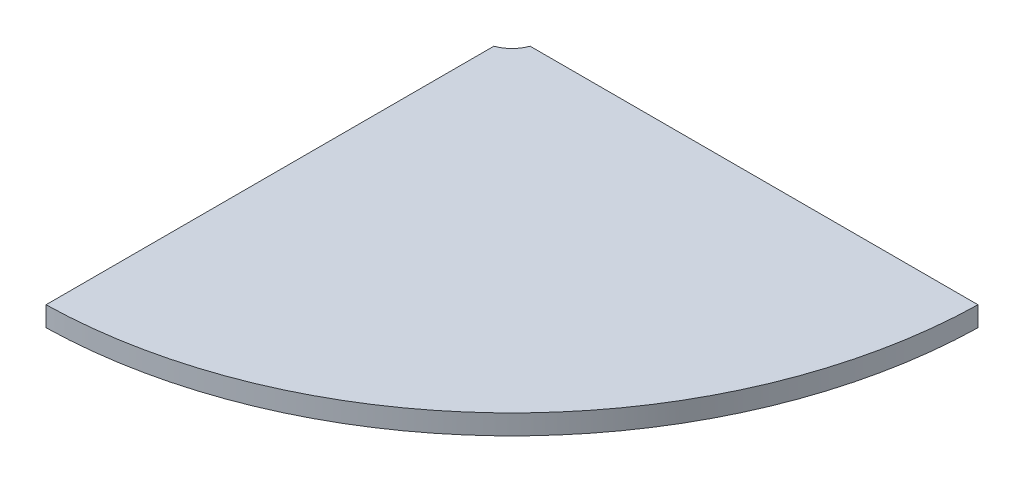
SolidWorks part; units mm, degrees
ref_plane "Alzado" through (0, 0, 0) normal (0, 0, 1) x (1, 0, 0)
ref_plane "Planta" through (0, 0, 0) normal (0, 1, 0) x (1, 0, 0)
ref_plane "Vista lateral" through (0, 0, 0) normal (1, 0, 0) x (0, 0, -1)
sketch "Croquis1" plane through (0, 0, 0) normal (0, 1, 0) x (1, 0, 0)
  line L0 (238.9081, -4.8752) -> (14.0133, -4.8752)
  line L1 (4.9081, -13.9804) -> (4.9081, -238.8752)
  line L2 (238.9081, -4.8752) -> (4.9081, -4.8752) construction
  line L3 (4.9081, -4.8752) -> (4.9081, -238.8752) construction
  arc A0 (4.9081, -238.8752) -> (238.9081, -4.8752) centre (-0.0718, 0.1047) ccw
  arc A1 (4.9081, -13.9804) -> (14.0133, -4.8752) centre (-0.0718, 0.1047) ccw
  dimension "D1" = 234
extrude "Saliente-Extruir1" add sketch "Croquis1" along normal blind 10
